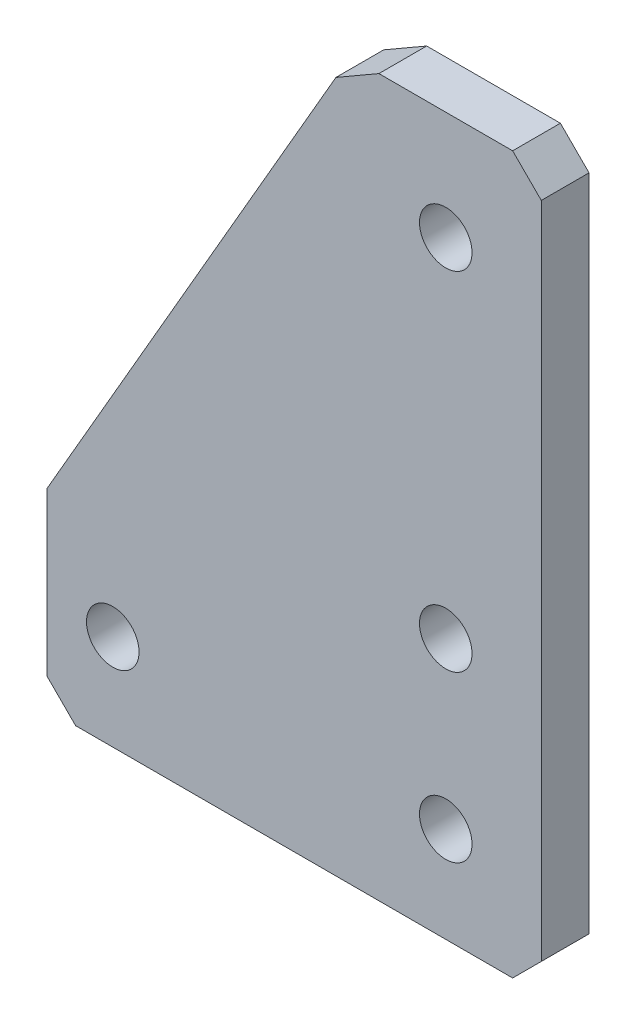
SolidWorks part; units mm, degrees
ref_plane "Front Plane" through (0, 0, 0) normal (0, 0, 1) x (1, 0, 0)
ref_plane "Top Plane" through (0, 0, 0) normal (0, 1, 0) x (1, 0, 0)
ref_plane "Right Plane" through (0, 0, 0) normal (1, 0, 0) x (0, 0, -1)
ref_plane "Plane1" through (0, 0, 847.2567) normal (0, 0, 1) x (1, 0, 0)
sketch "Sketch1" plane through (0, 0, 847.2567) normal (0, 0, 1) x (1, 0, 0)
  line L0 (445.3311, -16.9407) -> (425.3311, -16.9407)
  line L2 (425.3311, -16.9407) -> (393.5768, -71.9407)
  line L3 (393.5768, -71.9407) -> (393.5768, -91.9407)
  line L5 (393.5768, -91.9407) -> (445.3311, -91.9407)
  line L6 (445.3311, -91.9407) -> (445.3311, -16.9407)
  circle A0 centre (435.3311, -28.3117) radius 2.75
  circle A1 centre (435.3311, -64.6632) radius 2.75
  circle A2 centre (400.4696, -81.9407) radius 2.75
  circle A3 centre (435.3311, -81.9407) radius 2.75
  point P13 (435.3311, -16.9407)
  point P16 (393.5768, -81.9407)
  dimension "D5" = 5.5
  dimension "D6" = 5.5
  dimension "D7" = 5.5
  dimension "D8" = 5.5
  dimension "D1" = 20
  dimension "D2" = 20
  dimension "D3" = 75
  dimension "D4" = 150
extrude "Boss-Extrude1" add sketch "Sketch1" against normal blind 5
chamfer "Chamfer1" distance 3 4 edges at (445.3311, -91.9407, 844.7567) (393.5768, -91.9407, 844.7567) (445.3311, -16.9407, 844.7567) (425.3311, -16.9407, 844.7567)
